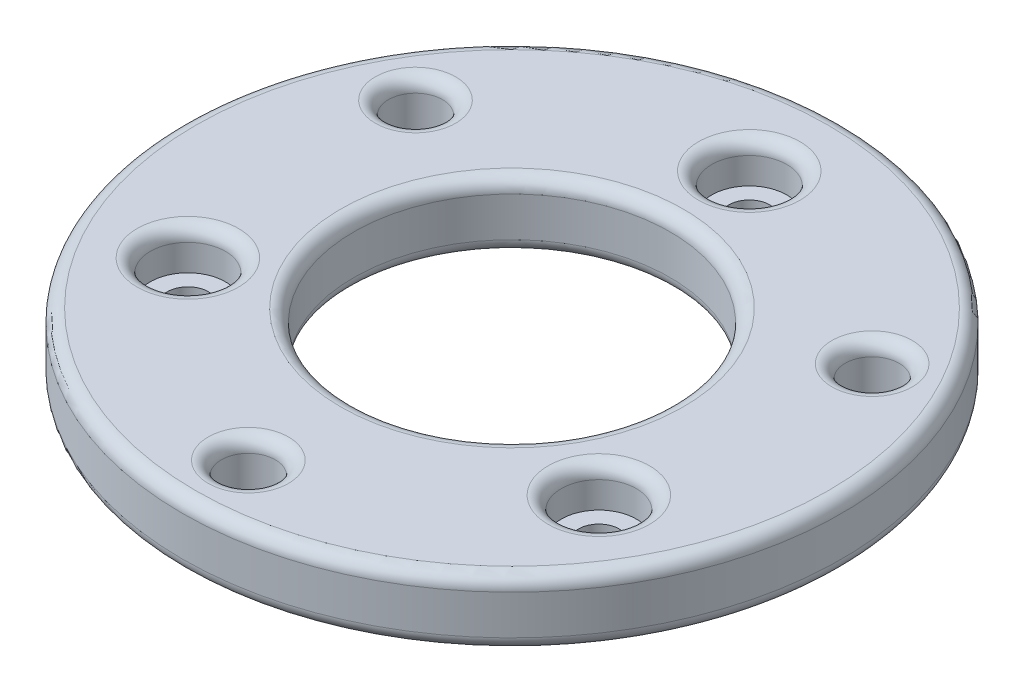
SolidWorks part; units mm, degrees
material "Nylon 101"
ref_plane "Front Plane" through (0, 0, 0) normal (0, 0, 1) x (1, 0, 0)
ref_plane "Top Plane" through (0, 0, 0) normal (0, 1, 0) x (1, 0, 0)
ref_plane "Right Plane" through (0, 0, 0) normal (1, 0, 0) x (0, 0, -1)
sketch "Sketch1" plane through (0, 0, 0) normal (0, 1, 0) x (1, 0, 0)
  line L0 (0, 0) -> (0, 37.9484) construction
  circle A0 centre (0, 0) radius 25
  circle A1 centre (0, 0) radius 12
  circle A2 centre (0, 18) radius 1.55
  circle A3 centre (15.5885, -9) radius 1.55
  circle A4 centre (-15.5885, -9) radius 1.55
  circle A5 centre (0, -20) radius 2.05
  circle A6 centre (-17.3205, 10) radius 2.05
  circle A7 centre (17.3205, 10) radius 2.05
  point P13 (0, 0)
  dimension "D1" = 24
  dimension "D2" = 50
  dimension "D3" = 3.1
  dimension "D4" = 18
  dimension "D6" = 20
  dimension "D7" = 4.1
  dimension "D5" = 3
extrude "Boss-Extrude1" add sketch "Sketch1" along normal blind 5
sketch "Sketch2" plane through (0, 5, 0) normal (0, 1, 0) x (1, 0, 0)
  circle A0 centre (0, 18) radius 2.85
  circle A1 centre (15.5885, -9) radius 2.85
  circle A2 centre (-15.5885, -9) radius 2.85
  point P9 (0, 0)
  dimension "D1" = 5.7
  dimension "D2" = 3
extrude "Cut-Extrude1" cut sketch "Sketch2" against normal blind 3
fillet "Fillet1" radius 1 16 edges at (-15.5885, 0, 10.55) (15.5885, 0, 10.55) (0, 0, -16.45) (0, 0, 12) (0, 0, 25) (0, 5, 25) (0, 5, 12) (-15.5885, 5, 11.85) (15.5885, 5, 11.85) (0, 5, -15.15) (17.3205, 0, -7.95) (-17.3205, 0, -7.95) (0, 0, 22.05) (17.3205, 5, -7.95) (0, 5, 22.05) (-17.3205, 5, -7.95)
